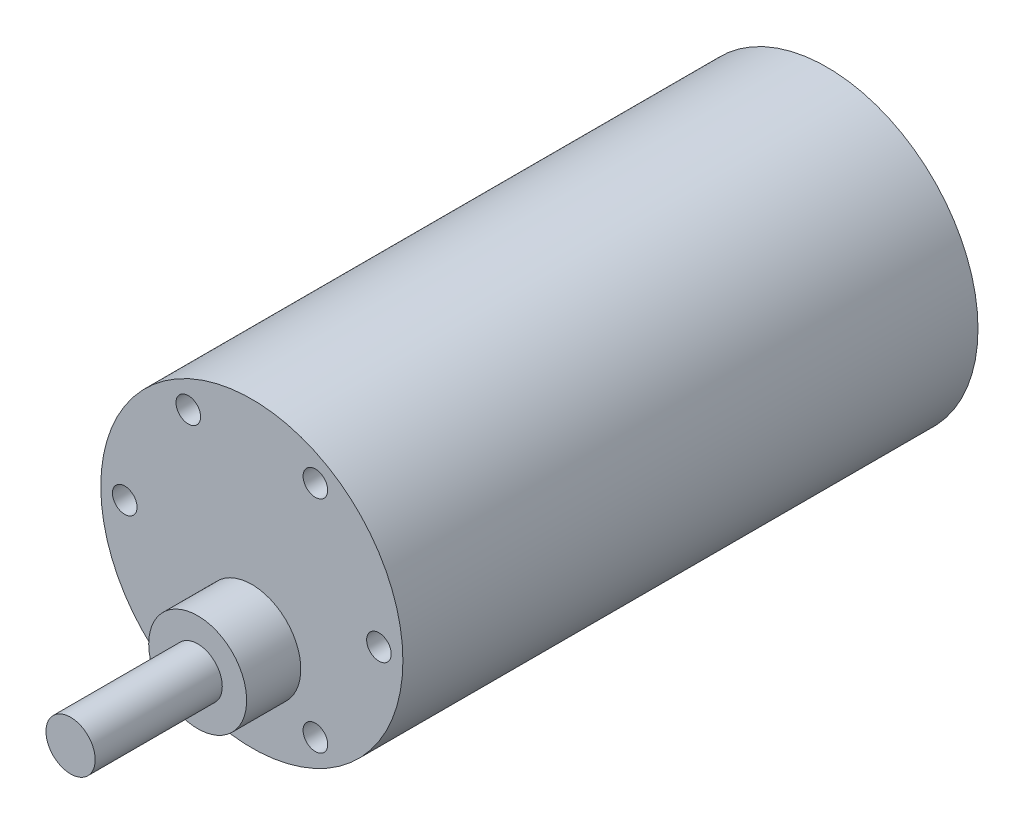
SolidWorks part; units mm, degrees
ref_plane "Front Plane" through (0, 0, 0) normal (0, 0, 1) x (1, 0, 0)
ref_plane "Top Plane" through (0, 0, 0) normal (0, 1, 0) x (1, 0, 0)
ref_plane "Right Plane" through (0, 0, 0) normal (1, 0, 0) x (0, 0, -1)
sketch "Sketch1" plane through (0, 0, 0) normal (0, 0, 1) x (1, 0, 0)
  circle A0 centre (0, 0) radius 18.415
  dimension "D1" = 36.83
extrude "Boss-Extrude1" add sketch "Sketch1" along normal blind 70.104
sketch "Sketch2" plane through (0, 0, 70.104) normal (0, 0, 1) x (1, 0, 0)
  line L0 (-18.415, 0) -> (18.415, 0) construction
  line L1 (0, 18.415) -> (0, -18.415) construction
  circle A0 centre (0, 0) radius 18.415 construction
  circle A1 centre (0, -7.112) radius 5.969
  dimension "D2" = 11.938
  dimension "D1" = 7.112
extrude "Boss-Extrude2" add sketch "Sketch2" along normal blind 6.604
sketch "Sketch3" plane through (0, 0, 76.708) normal (0, 0, 1) x (1, 0, 0)
  line L0 (0, -1.143) -> (0, -13.081) construction
  line L1 (-5.969, -7.112) -> (5.969, -7.112) construction
  circle A1 centre (0, -7.112) radius 5.969 construction
  circle A2 centre (0, -7.112) radius 5.969 construction
  circle A3 centre (0, -7.112) radius 3
  point P11 (-0.1842, -7.112)
  dimension "D1" = 6
extrude "Boss-Extrude3" add sketch "Sketch3" along normal blind 15.494
sketch "Sketch4" plane through (0, 0, 70.104) normal (0, 0, 1) x (1, 0, 0)
  line L0 (-18.415, 0) -> (18.415, 0) construction
  circle A0 centre (0, 0) radius 15.494 construction
  circle A1 centre (0, 0) radius 18.415 construction
  circle A2 centre (-15.494, 0) radius 1.5
  circle A3 centre (15.494, 0) radius 1.5
  circle A4 centre (7.747, 13.4182) radius 1.5
  circle A5 centre (-7.747, 13.4182) radius 1.5
  circle A6 centre (-7.747, -13.4182) radius 1.5
  circle A7 centre (7.747, -13.4182) radius 1.5
  point P8 (-15.494, 0)
  point P9 (15.494, 0)
  dimension "D1" = 30.988
  dimension "D2" = 3
  dimension "D3" = 15.494
  dimension "D4" = 15.494
  dimension "D5" = 15.494
  dimension "D6" = 15.494
extrude "Cut-Extrude1" cut sketch "Sketch4" against normal blind 25.4
